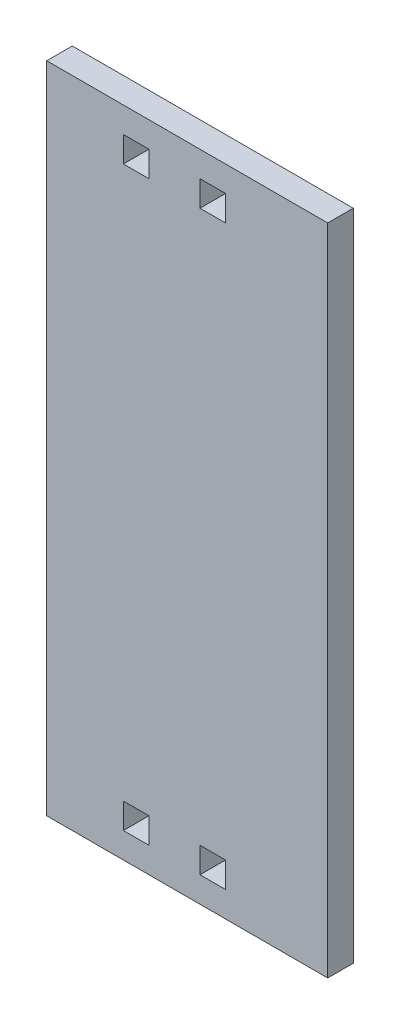
SolidWorks part; units mm, degrees
ref_plane "Plan de face" through (0, 0, 0) normal (0, 0, 1) x (1, 0, 0)
ref_plane "Plan de dessus" through (0, 0, 0) normal (0, 1, 0) x (1, 0, 0)
ref_plane "Plan de droite" through (0, 0, 0) normal (1, 0, 0) x (0, 0, -1)
sketch "Esquisse1" plane through (0, 0, 0) normal (0, 0, 1) x (1, 0, 0)
  line L0 (-25, -7.5) -> (-25, 120.5) construction
  line L1 (-25, 120.5) -> (25, 120.5)
  line L2 (25, 120.5) -> (25, -7.5) construction
  line L3 (25, -7.5) -> (-25, -7.5)
  line L4 (-25, 56.5) -> (25, 56.5) construction
  line L5 (-25, 120.5) -> (-25, 56.5)
  line L6 (-25, 56.5) -> (-25, -7.5)
  line L7 (25, 120.5) -> (30, 120.5)
  line L8 (30, 120.5) -> (30, -7.5)
  line L9 (30, -7.5) -> (25, -7.5)
  line B0 (-5, 0) -> (5, 0) construction
  line B1 (-5, 2.5) -> (-10, 2.5)
  line B2 (-5, 2.5) -> (-5, -2.5)
  line B3 (-5, -2.5) -> (-10, -2.5)
  line B4 (-10, 2.5) -> (-10, -2.5)
  line B5 (5, 2.5) -> (10, 2.5)
  line B6 (5, 2.5) -> (5, -2.5)
  line B7 (5, -2.5) -> (10, -2.5)
  line B8 (10, 2.5) -> (10, -2.5)
  line B9 (0, 0) -> (0, 6.9724) construction
  circle B10 centre (0, 0) radius 2 construction
  line B11 (-5, 113) -> (5, 113) construction
  line B12 (-5, 110.5) -> (-10, 110.5)
  line B13 (-5, 110.5) -> (-5, 115.5)
  line B14 (-5, 115.5) -> (-10, 115.5)
  line B15 (-10, 110.5) -> (-10, 115.5)
  line B16 (5, 110.5) -> (10, 110.5)
  line B17 (5, 110.5) -> (5, 115.5)
  line B18 (5, 115.5) -> (10, 115.5)
  line B19 (10, 110.5) -> (10, 115.5)
  line B20 (0, 113) -> (0, 106.0276) construction
  circle B21 centre (0, 113) radius 2 construction
  dimension "D1" = 5
  dimension "D2" = 15
  dimension "D3" = 15
  dimension "D4" = 108
  dimension "D6" = 5
sketch_block_instance "Trou M4 plots 5mm-1"
sketch_block "Trou M4 plots 5mm" parameters "D2"=4, "D5"=4, "D1"=5, "D3"=5, "D4"=10
sketch_block_instance "Trou M4 plots 5mm-3"
extrude "Boss.-Extru.1" add sketch "Esquisse1" along normal blind 5
